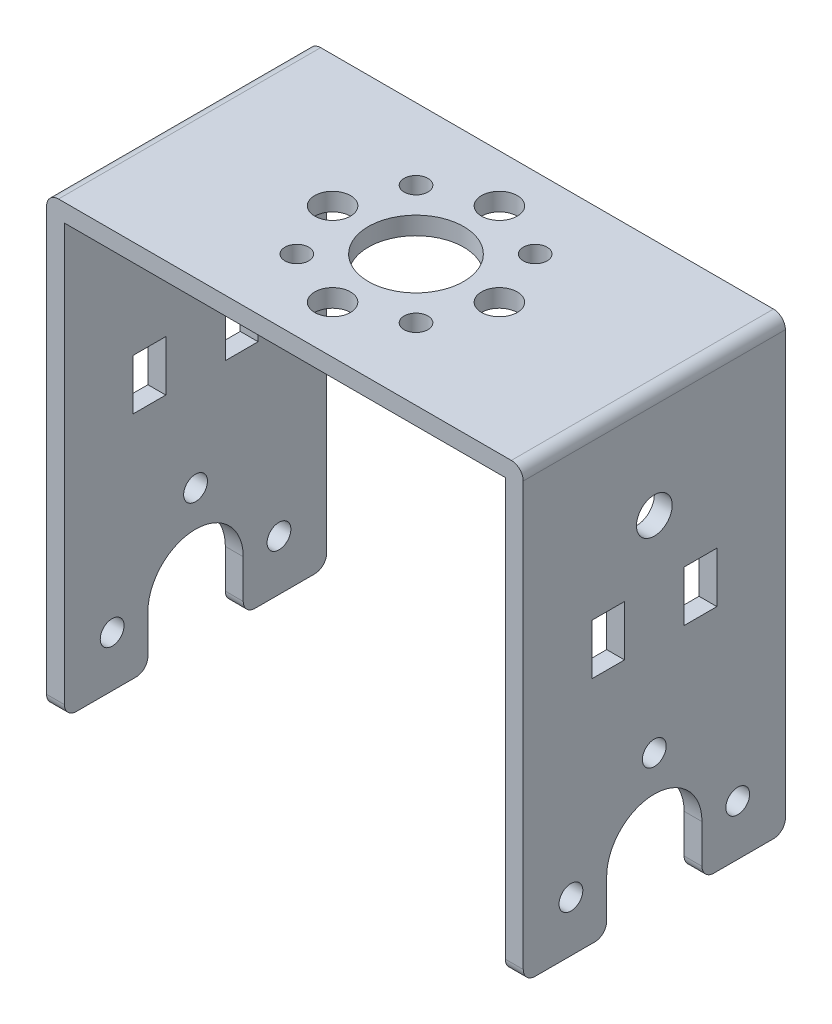
SolidWorks part; units mm, degrees
material "Plain Carbon Steel"
ref_plane "Front Plane" through (0, 0, 0) normal (0, 0, 1) x (1, 0, 0)
ref_plane "Top Plane" through (0, 0, 0) normal (0, 1, 0) x (1, 0, 0)
ref_plane "Right Plane" through (0, 0, 0) normal (1, 0, 0) x (0, 0, -1)
sketch "Sketch1" plane through (0, 0, 0) normal (0, 1, 0) x (1, 0, 0)
  line L1 (-20, 11) -> (20, 11)
  line L2 (-20, 11) -> (-20, -11)
  line L3 (-20, -11) -> (20, -11)
  line L4 (20, 11) -> (20, -11)
  line L5 (-20, 11) -> (20, -11) construction
  line L6 (-20, -11) -> (20, 11) construction
  circle A0 centre (0, 0) radius 4
  circle A1 centre (0, 7) radius 1.5
  circle A2 centre (7, 0) radius 1.5
  circle A3 centre (0, -7) radius 1.5
  circle A4 centre (-7, 0) radius 1.5
  circle A5 centre (5, 5) radius 1
  circle A6 centre (5, -5) radius 1
  circle A7 centre (-5, -5) radius 1
  circle A8 centre (-5, 5) radius 1
  circle A9 centre (0, 0) radius 7 construction
  point P0 (0, 0)
  point P19 (0, 0)
  point P28 (0, 0)
  dimension "D3" = 8
  dimension "D4" = 3
  dimension "D7" = 4
  dimension "D8" = 13
  dimension "D10" = 2
  dimension "D14" = 15
  dimension "D16" = 14
  dimension "D1" = 40
  dimension "D2" = 22
  dimension "D5" = 4
  dimension "D6" = 20
  dimension "D9" = 13
  dimension "D11" = 5
  dimension "D12" = 5
  dimension "D15" = 6
  dimension "D13" = 4
extrude "Boss-Extrude1" add sketch "Sketch1" along normal blind 1.5
sketch "Sketch2" plane through (0, 0, 0) normal (0, -1, 0) x (-1, 0, 0)
  line L0 (20, -11) -> (-20, -11) construction
  line L1 (-20, 11) -> (-18.5, 11)
  line L2 (-20, 11) -> (-20, -11)
  line L3 (-20, -11) -> (-18.5, -11)
  line L4 (-18.5, 11) -> (-18.5, -11)
  dimension "D1" = 1.5
extrude "Boss-Extrude2" add sketch "Sketch2" along normal blind 36
mirror "Mirror1" about plane through (0, 0, 0) normal (1, 0, 0) of "Boss-Extrude2"
fillet "Fillet1" radius 1 2 edges at (20, 1.5, 0) (-20, 1.5, 0)
sketch "Sketch3" plane through (-20, 0, 0) normal (-1, 0, 0) x (0, 0, 1)
  line L0 (-11, 0.5) -> (-11, -36) construction
  line L1 (-11, 1.5) -> (11, 1.5) construction
  line L2 (-4, -31.75) -> (-4, -36)
  line L3 (-5.25, -12.5) -> (-2.5, -12.5)
  line L4 (-5.25, -12.5) -> (-5.25, -16.75)
  line L5 (-5.25, -16.75) -> (-2.5, -16.75)
  line L6 (-2.5, -12.5) -> (-2.5, -16.75)
  line L7 (2.5, -12.5) -> (5.25, -12.5)
  line L8 (2.5, -12.5) -> (2.5, -16.75)
  line L9 (2.5, -16.75) -> (5.25, -16.75)
  line L10 (5.25, -12.5) -> (5.25, -16.75)
  line L11 (-11, -36) -> (11, -36) construction
  line L12 (4, -31.75) -> (4, -36)
  line L13 (11, 0.5) -> (11, -36) construction
  line L14 (4, -36) -> (-4, -36)
  circle A0 centre (0, -7.5) radius 1.5
  circle A1 centre (0, -24.75) radius 1
  circle A2 centre (-7, -31.75) radius 1
  circle A3 centre (7, -31.75) radius 1
  arc A4 (4, -31.75) -> (-4, -31.75) centre (0, -31.75) ccw
  dimension "D1" = 3
  dimension "D10" = 2
  dimension "D15" = 4
  dimension "D17" = 8
  dimension "D2" = 11
  dimension "D3" = 9
  dimension "D4" = 2.75
  dimension "D5" = 2.75
  dimension "D6" = 5
  dimension "D7" = 5.75
  dimension "D8" = 5
  dimension "D9" = 4.25
  dimension "D11" = 8
  dimension "D12" = 11
  dimension "D13" = 7
  dimension "D14" = 7
  dimension "D16" = 4
  dimension "D18" = 4.25
  dimension "D19" = 7
extrude "Cut-Extrude1" cut sketch "Sketch3" against normal through all
fillet "Fillet2" radius 1 8 edges at (-19.25, -36, -4) (-19.25, -36, -11) (-19.25, -36, 4) (-19.25, -36, 11) (19.25, -36, 11) (19.25, -36, 4) (19.25, -36, -4) (19.25, -36, -11)
